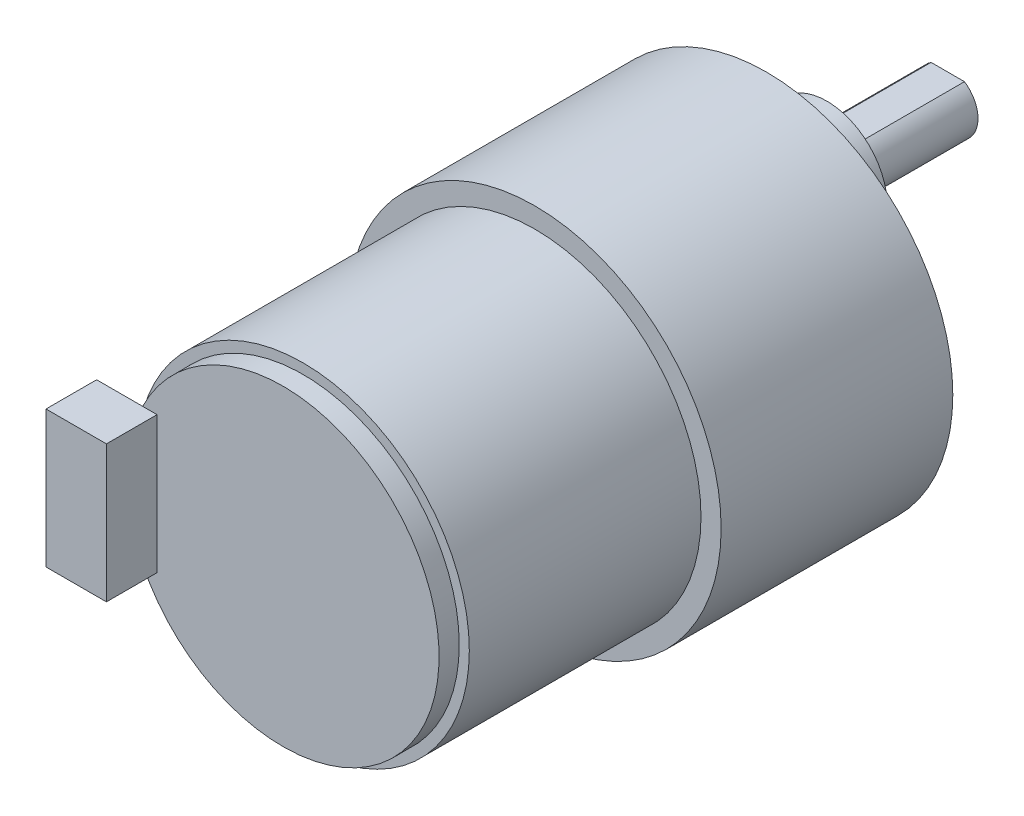
SolidWorks part; units mm, degrees
ref_plane "Front Plane" through (0, 0, 0) normal (0, 0, 1) x (1, 0, 0)
ref_plane "Top Plane" through (0, 0, 0) normal (0, 1, 0) x (1, 0, 0)
ref_plane "Right Plane" through (0, 0, 0) normal (1, 0, 0) x (0, 0, -1)
sketch "Sketch1" plane through (0, 0, 0) normal (0, 0, 1) x (1, 0, 0)
  circle A0 centre (0, 0) radius 16.5
  dimension "D1" = 33
extrude "Boss-Extrude1" add sketch "Sketch1" against normal blind 23
sketch "Sketch2" plane through (0, 0, -23) normal (0, 0, -1) x (-1, 0, 0)
  circle A0 centre (0, 0) radius 18.5
  dimension "D1" = 37
extrude "Boss-Extrude2" add sketch "Sketch2" along normal blind 23
sketch "Sketch3" plane through (0, 0, -46) normal (0, 0, -1) x (-1, 0, 0)
  line L0 (0, 12.65) -> (0, -12.65) construction
  line L1 (12.65, 0) -> (-12.65, 0) construction
  circle A0 centre (0, 7) radius 6
  dimension "D1" = 12
  dimension "D2" = 7
extrude "Boss-Extrude3" add sketch "Sketch3" along normal blind 6
sketch "Sketch4" plane through (0, 0, -52) normal (0, 0, -1) x (-1, 0, 0)
  line L0 (-1.6583, 9.5) -> (1.6583, 9.5)
  arc A0 (-1.6583, 9.5) -> (1.6583, 9.5) centre (0, 7) ccw
  dimension "D1" = 6
  dimension "D2" = 2.5
extrude "Boss-Extrude4" add sketch "Sketch4" along normal blind 12
sketch "Sketch5" plane through (0, 0, -46) normal (0, 0, -1) x (-1, 0, 0)
  circle A0 centre (0, 0) radius 15.5 construction
  dimension "D1" = 31
hole_wizard "M3x0.5 Tapped Hole1" positions "Sketch6" profile "Sketch7" tap size "M3x0.5" standard "ANSI Metric"
sketch "Sketch6" plane through (0, 0, -46) normal (0, 0, -1) x (-1, 0, 0)
  circle A1 centre (0, 0) radius 15.5 construction
  point P7 (15.5, 0)
cosmetic thread "Hole Thread1" parameters "D1"=10, "D2"=3
sketch "Sketch7" plane through (-15.5, 0, -46) normal (1, 0, 0) x (0, 1, 0)
  line L0 (0, 0) -> (0, 10.7511)
  line L1 (0, 10.7511) -> (1.25, 10)
  line L2 (1.25, 10) -> (1.25, 0.275)
  line L3 (1.25, 0.275) -> (1.525, 0)
  line L5 (1.525, 0) -> (0, 0)
  line L6 (-1.25, 0.275) -> (-1.525, 0) construction
  line L10 (0, 10.7511) -> (-1.25, 10) construction
  line L11 (0, -6.35) -> (0, 107.95) construction
  dimension "Tap Drill Dia." = 2.5
  dimension "Tap Drill Depth" = 10
  dimension "Near C'Sink Dia." = 3.05
  dimension "Near C'Sink Angle" = 90
  dimension "Drill Angle" = 118
pattern_circular "CirPattern1" count 6 over 360 about axis through (0, 0, 0) along (0, 0, 1) of "M3x0.5 Tapped Hole1"
sketch "Sketch8" plane through (0, 0, 0) normal (0, 0, 1) x (1, 0, 0)
  circle A0 centre (0, 0) radius 15.5
extrude "Boss-Extrude5" add sketch "Sketch8" along normal blind 2
sketch "Sketch11" plane through (0, 0, -46) normal (0, 0, -1) x (-1, 0, 0)
  circle A0 centre (0, 0) radius 18.5 construction
  point P0 (18.5, 0)
ref_plane "Plane1" through (-18.5, 0, 0) normal (1, 0, 0) x (0, 0, -1)
sketch "Sketch10" plane through (0, 0, 2) normal (0, 0, 1) x (1, 0, 0)
  line L0 (-18.5, -20.35) -> (-18.5, 20.35) construction
  line L1 (-12.5, -6.7929) -> (-18.5, -6.7929)
  line L2 (-12.5, -6.7929) -> (-12.5, 6.7929)
  line L3 (-12.5, 6.7929) -> (-18.5, 6.7929)
  line L4 (-18.5, -6.7929) -> (-18.5, 6.7929)
  line L5 (-12.5, -6.7929) -> (-18.5, 6.7929) construction
  line L6 (-12.5, 6.7929) -> (-18.5, -6.7929) construction
  circle A0 centre (0, 0) radius 15.5 construction
  point P0 (-15.5, 0)
extrude "Boss-Extrude6" add sketch "Sketch10" along normal blind 5.025 contours L2 L3 L4 L1
